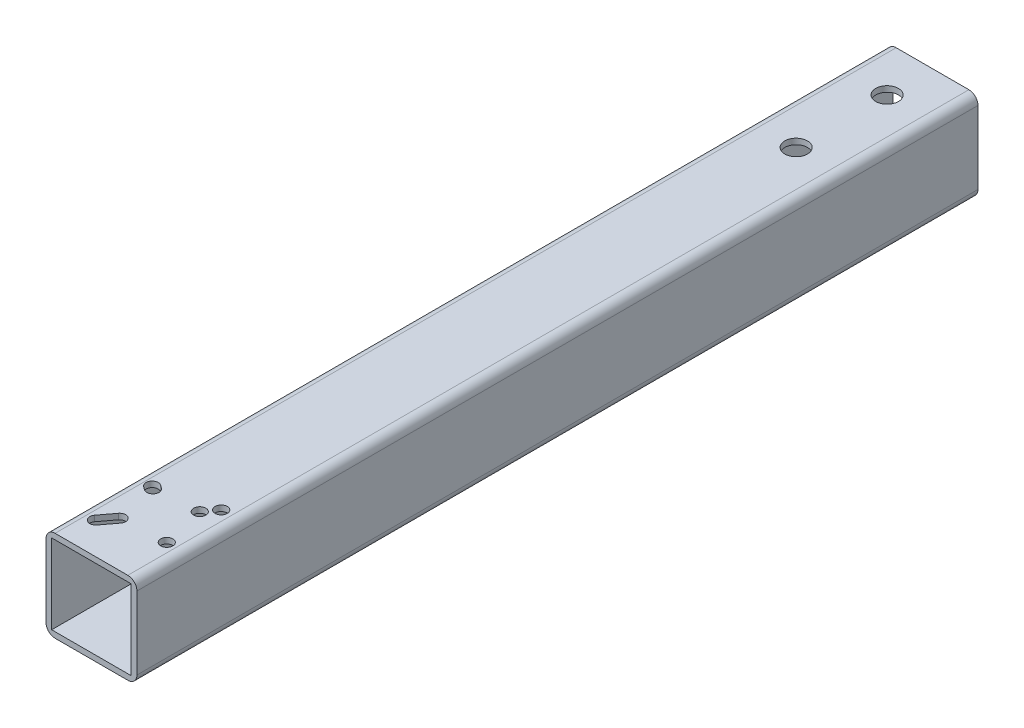
SolidWorks part; units mm, degrees
ref_plane "Front Plane" through (0, 0, 0) normal (0, 0, 1) x (1, 0, 0)
ref_plane "Top Plane" through (0, 0, 0) normal (0, 1, 0) x (1, 0, 0)
ref_plane "Right Plane" through (0, 0, 0) normal (1, 0, 0) x (0, 0, -1)
sketch "Sketch1" plane through (0, 0, 0) normal (0, 0, 1) x (1, 0, 0)
  line L1 (-24.2596, 11.4248) -> (1.1404, 11.4248)
  line L2 (-24.2596, 11.4248) -> (-24.2596, -13.9752)
  line L3 (-24.2596, -13.9752) -> (1.1404, -13.9752)
  line L4 (1.1404, 11.4248) -> (1.1404, -13.9752)
  line L5 (-22.6721, 9.8373) -> (-0.4471, 9.8373)
  line L6 (-22.6721, 9.8373) -> (-22.6721, -12.3877)
  line L7 (-22.6721, -12.3877) -> (-0.4471, -12.3877)
  line L8 (-0.4471, 9.8373) -> (-0.4471, -12.3877)
  dimension "D1" = 25.4
  dimension "D2" = 25.4
  dimension "D3" = 1.5875
  dimension "D4" = 1.5875
  dimension "D5" = 1.5875
  dimension "D6" = 1.5875
extrude "Boss-Extrude1" add sketch "Sketch1" along normal blind 234.95
fillet "Fillet1" radius 2.54 4 edges at (1.1404, -13.9752, 117.475) (-24.2596, -13.9752, 117.475) (-24.2596, 11.4248, 117.475) (1.1404, 11.4248, 117.475)
sketch "Sketch2" plane through (0, 11.4248, 0) normal (0, 1, 0) x (1, 0, 0)
  line L0 (-1.3996, 0) -> (-21.7196, 0) construction
  line L1 (0, 0) -> (0, -59.7417) construction
  line L2 (-11.5596, -12.7) -> (-11.5596, 0) construction
  line L3 (-1.3996, -234.95) -> (-1.3996, 0) construction
  line L4 (-21.7196, -50.8) -> (29.3119, -50.8) construction
  line L5 (-21.7196, 0) -> (-21.7196, -234.95) construction
  circle A0 centre (-11.5596, -12.7) radius 3.175
  circle A2 centre (-11.5596, -38.1) radius 3.175
  dimension "D1" = 6.35
  dimension "D2" = 12.7
  dimension "D3" = 6.35
  dimension "D4" = 50.8
  dimension "D6" = 25.4
extrude "Cut-Extrude1" cut sketch "Sketch2" against normal through all
sketch "Sketch3" plane through (0, 11.4248, 0) normal (0, 1, 0) x (1, 0, 0)
  line L0 (-11.5596, -215.9) -> (-15.3182, -190.7796) construction
  line L1 (-11.5596, -215.9) -> (13.426, -212.1616) construction
  line L2 (-11.5596, -215.9) -> (-29.2422, -202.8202) construction
  line L3 (-11.5596, -215.9) -> (2.8538, -196.7728) construction
  line L4 (-11.5596, -12.7) -> (-11.5596, -270.3313) construction
  line L5 (-16.3741, -222.2891) -> (-19.2175, -226.0624) construction
  line L6 (-15.0164, -223.3122) -> (-17.8598, -227.0855)
  line L7 (-17.7318, -221.266) -> (-20.5752, -225.0393)
  line L8 (-19.6056, -209.9484) -> (-18.7888, -210.5526) construction
  line L9 (-18.5946, -208.5816) -> (-17.7778, -209.1858)
  line L10 (-20.6166, -211.3151) -> (-19.7997, -211.9193)
  line L11 (-11.5596, -215.9) -> (30.1254, -215.9) construction
  line L12 (-37.8321, -50.8) -> (104.3326, -50.8) construction
  line L13 (-1.3996, 0) -> (-21.7196, 0) construction
  circle A0 centre (-6.7451, -209.5109) radius 1.7
  circle A1 centre (-4.1721, -206.0965) radius 1.7
  circle A2 centre (-11.5596, -215.9) radius 20.9 construction
  circle A3 centre (-3.922, -221.5495) radius 1.7
  arc A4 (-18.5946, -208.5816) -> (-20.6166, -211.3151) centre (-19.6056, -209.9484) ccw
  arc A5 (-19.7997, -211.9193) -> (-17.7778, -209.1858) centre (-18.7888, -210.5526) ccw
  arc A6 (-15.0164, -223.3122) -> (-17.7318, -221.266) centre (-16.3741, -222.2891) ccw
  arc A7 (-20.5752, -225.0393) -> (-17.8598, -227.0855) centre (-19.2175, -226.0624) ccw
  point P17 (-11.5596, -196.9907)
  point P21 (-17.7958, -224.1758)
  point P27 (-19.1972, -210.2505)
  point P33 (-11.5596, 0)
  point P34 (-20.2082, -211.6172)
  dimension "D1" = 215.9
  dimension "D2" = 3.4
  dimension "D3" = 3.4
  dimension "D4" = 3.4
  dimension "D13" = 41.8
  dimension "D5" = 3.4
  dimension "D6" = 3.4
  dimension "D7" = 16
  dimension "D8" = 25
  dimension "D9" = 19
  dimension "D10" = 8
  dimension "D11" = 9.5
  dimension "D12" = 9.5
  dimension "D14" = 50.8
extrude "Cut-Extrude2" cut sketch "Sketch3" against normal blind 2.54
